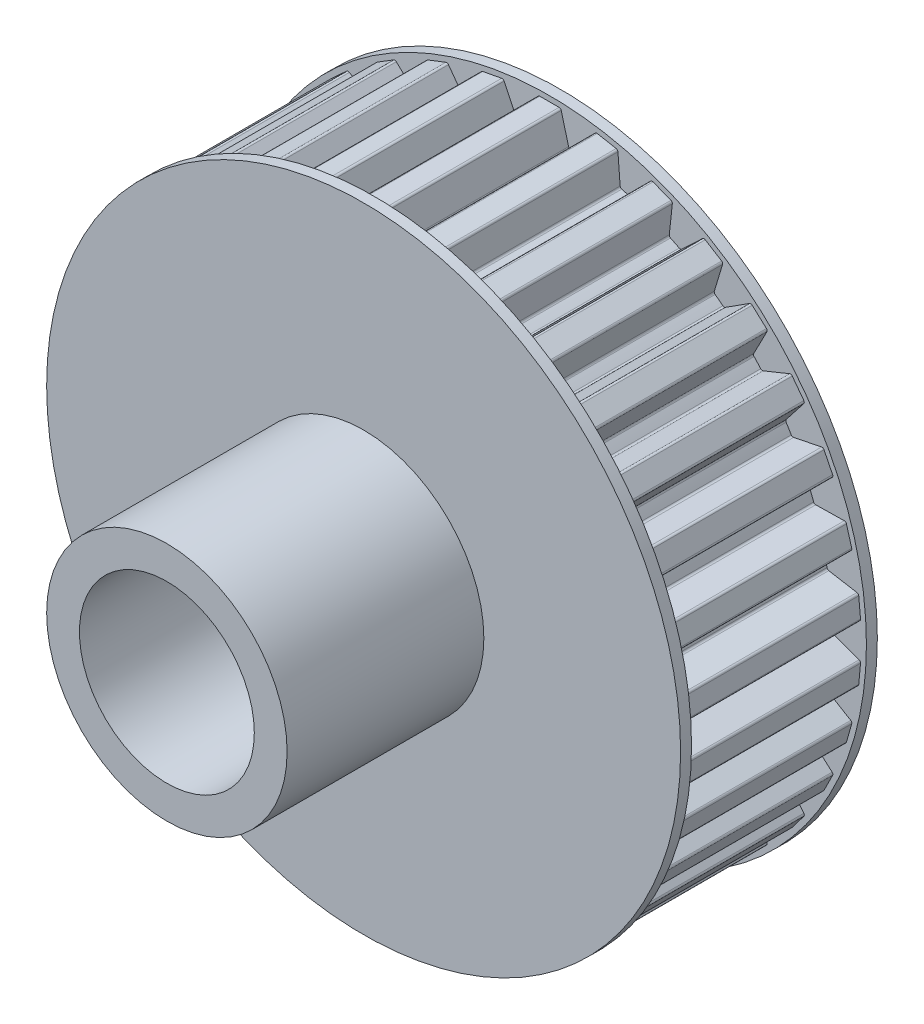
SolidWorks part; units mm, degrees
ref_plane "Plan de face" through (0, 0, 0) normal (0, 0, 1) x (1, 0, 0)
ref_plane "Plan de dessus" through (0, 0, 0) normal (0, 1, 0) x (1, 0, 0)
ref_plane "Plan de droite" through (0, 0, 0) normal (1, 0, 0) x (0, 0, -1)
sketch "Esquisse1" plane through (0, 0, 0) normal (0, 0, 1) x (1, 0, 0)
  line L0 (0, 21.7728) -> (0, 34.0588) construction
  line L1 (-1.0353, 28.5) -> (1.0353, 28.5)
  line L2 (1.0353, 28.5) -> (1.7888, 25.6878)
  line L3 (-25.75, 0) -> (30.4929, 0) construction
  line L4 (0, -28.5) -> (1.0353, -28.5)
  line L5 (0, 28.5) -> (1.7626, 21.9219) construction
  line L6 (-1.0353, 28.5) -> (-1.7888, 25.6878)
  line L7 (4.2192, 28.205) -> (2.9618, 25.5791)
  line L8 (4.2192, 28.205) -> (6.2545, 27.8245)
  line L9 (6.2545, 27.8245) -> (6.4785, 24.9217)
  line L10 (9.33, 26.9494) -> (7.6115, 24.5993)
  line L11 (9.33, 26.9494) -> (11.2608, 26.2015)
  line L12 (11.2608, 26.2015) -> (10.9475, 23.307)
  line L13 (14.1231, 24.7762) -> (12.002, 22.7819)
  line L14 (14.1231, 24.7762) -> (15.8835, 23.6862)
  line L15 (15.8835, 23.6862) -> (15.0438, 20.8985)
  line L16 (18.4352, 21.7592) -> (15.9838, 20.1886)
  line L17 (18.4352, 21.7592) -> (19.9654, 20.3643)
  line L18 (19.9654, 20.3643) -> (18.6277, 17.7784)
  line L19 (22.1196, 18.0013) -> (19.4213, 16.9079)
  line L20 (22.1196, 18.0013) -> (23.3674, 16.3489)
  line L21 (23.3674, 16.3489) -> (21.5773, 14.0529)
  line L22 (25.0507, 13.6303) -> (22.1974, 13.0513)
  line L23 (25.0507, 13.6303) -> (25.9736, 11.7768)
  line L24 (25.9736, 11.7768) -> (23.7921, 9.8488)
  line L25 (27.1287, 8.7952) -> (24.2176, 8.7503)
  line L26 (27.1287, 8.7952) -> (27.6953, 6.8036)
  line L27 (27.6953, 6.8036) -> (25.1967, 5.3093)
  line L28 (28.2829, 3.6605) -> (25.4132, 4.1513)
  line L29 (28.2829, 3.6605) -> (28.4739, 1.5988)
  line L30 (28.4739, 1.5988) -> (25.7433, 0.589)
  line L31 (28.4739, -1.5988) -> (25.7433, -0.589)
  line L32 (28.4739, -1.5988) -> (28.2829, -3.6605)
  line L33 (28.2829, -3.6605) -> (25.4132, -4.1513)
  line L34 (27.6953, -6.8036) -> (25.1967, -5.3093)
  line L35 (27.6953, -6.8036) -> (27.1287, -8.7952)
  line L36 (27.1287, -8.7952) -> (24.2176, -8.7503)
  line L37 (25.9736, -11.7768) -> (23.7921, -9.8488)
  line L38 (25.9736, -11.7768) -> (25.0507, -13.6303)
  line L39 (25.0507, -13.6303) -> (22.1974, -13.0513)
  line L40 (23.3674, -16.3489) -> (21.5773, -14.0529)
  line L41 (23.3674, -16.3489) -> (22.1196, -18.0013)
  line L42 (22.1196, -18.0013) -> (19.4213, -16.9079)
  line L43 (19.9654, -20.3643) -> (18.6277, -17.7784)
  line L44 (19.9654, -20.3643) -> (18.4352, -21.7592)
  line L45 (18.4352, -21.7592) -> (15.9838, -20.1886)
  line L46 (15.8835, -23.6862) -> (15.0438, -20.8985)
  line L47 (15.8835, -23.6862) -> (14.1231, -24.7762)
  line L48 (14.1231, -24.7762) -> (12.002, -22.7819)
  line L49 (11.2608, -26.2015) -> (10.9475, -23.307)
  line L50 (11.2608, -26.2015) -> (9.33, -26.9494)
  line L51 (9.33, -26.9494) -> (7.6115, -24.5993)
  line L52 (6.2545, -27.8245) -> (6.4785, -24.9217)
  line L53 (6.2545, -27.8245) -> (4.2192, -28.205)
  line L54 (4.2192, -28.205) -> (2.9618, -25.5791)
  line L55 (1.0353, -28.5) -> (1.7888, -25.6878)
  line L56 (1.0353, -28.5) -> (-1.0353, -28.5)
  line L57 (-1.0353, -28.5) -> (-1.7888, -25.6878)
  line L58 (-4.2192, -28.205) -> (-2.9618, -25.5791)
  line L59 (-4.2192, -28.205) -> (-6.2545, -27.8245)
  line L60 (-6.2545, -27.8245) -> (-6.4785, -24.9217)
  line L61 (-9.33, -26.9494) -> (-7.6115, -24.5993)
  line L62 (-9.33, -26.9494) -> (-11.2608, -26.2015)
  line L63 (-11.2608, -26.2015) -> (-10.9475, -23.307)
  line L64 (-14.1231, -24.7762) -> (-12.002, -22.7819)
  line L65 (-14.1231, -24.7762) -> (-15.8835, -23.6862)
  line L66 (-15.8835, -23.6862) -> (-15.0438, -20.8985)
  line L67 (-18.4352, -21.7592) -> (-15.9838, -20.1886)
  line L68 (-18.4352, -21.7592) -> (-19.9654, -20.3643)
  line L69 (-19.9654, -20.3643) -> (-18.6277, -17.7784)
  line L70 (-22.1196, -18.0013) -> (-19.4213, -16.9079)
  line L71 (-22.1196, -18.0013) -> (-23.3674, -16.3489)
  line L72 (-23.3674, -16.3489) -> (-21.5773, -14.0529)
  line L73 (-25.0507, -13.6303) -> (-22.1974, -13.0513)
  line L74 (-25.0507, -13.6303) -> (-25.9736, -11.7768)
  line L75 (-25.9736, -11.7768) -> (-23.7921, -9.8488)
  line L76 (-27.1287, -8.7952) -> (-24.2176, -8.7503)
  line L77 (-27.1287, -8.7952) -> (-27.6953, -6.8036)
  line L78 (-27.6953, -6.8036) -> (-25.1967, -5.3093)
  line L79 (-28.2829, -3.6605) -> (-25.4132, -4.1513)
  line L80 (-28.2829, -3.6605) -> (-28.4739, -1.5988)
  line L81 (-28.4739, -1.5988) -> (-25.7433, -0.589)
  line L82 (-28.4739, 1.5988) -> (-25.7433, 0.589)
  line L83 (-28.4739, 1.5988) -> (-28.2829, 3.6605)
  line L84 (-28.2829, 3.6605) -> (-25.4132, 4.1513)
  line L85 (-27.6953, 6.8036) -> (-25.1967, 5.3093)
  line L86 (-27.6953, 6.8036) -> (-27.1287, 8.7952)
  line L87 (-27.1287, 8.7952) -> (-24.2176, 8.7503)
  line L88 (-25.9736, 11.7768) -> (-23.7921, 9.8488)
  line L89 (-25.9736, 11.7768) -> (-25.0507, 13.6303)
  line L90 (-25.0507, 13.6303) -> (-22.1974, 13.0513)
  line L91 (-23.3674, 16.3489) -> (-21.5773, 14.0529)
  line L92 (-23.3674, 16.3489) -> (-22.1196, 18.0013)
  line L93 (-22.1196, 18.0013) -> (-19.4213, 16.9079)
  line L94 (-19.9654, 20.3643) -> (-18.6277, 17.7784)
  line L95 (-19.9654, 20.3643) -> (-18.4352, 21.7592)
  line L96 (-18.4352, 21.7592) -> (-15.9838, 20.1886)
  line L97 (-15.8835, 23.6862) -> (-15.0438, 20.8985)
  line L98 (-15.8835, 23.6862) -> (-14.1231, 24.7762)
  line L99 (-14.1231, 24.7762) -> (-12.002, 22.7819)
  line L100 (-11.2608, 26.2015) -> (-10.9475, 23.307)
  line L101 (-11.2608, 26.2015) -> (-9.33, 26.9494)
  line L102 (-9.33, 26.9494) -> (-7.6115, 24.5993)
  line L103 (-6.2545, 27.8245) -> (-6.4785, 24.9217)
  line L104 (-6.2545, 27.8245) -> (-4.2192, 28.205)
  line L105 (-4.2192, 28.205) -> (-2.9618, 25.5791)
  circle A0 centre (0, 0) radius 6
  arc A1 (-1.7888, 25.6878) -> (-2.9618, 25.5791) centre (0, 0) ccw
  arc A2 (-6.4785, 24.9217) -> (-7.6115, 24.5993) centre (0, 0) ccw
  arc A3 (-10.9475, 23.307) -> (-12.002, 22.7819) centre (0, 0) ccw
  arc A4 (-15.0438, 20.8985) -> (-15.9838, 20.1886) centre (0, 0) ccw
  arc A5 (-18.6277, 17.7784) -> (-19.4213, 16.9079) centre (0, 0) ccw
  arc A6 (-21.5773, 14.0529) -> (-22.1974, 13.0513) centre (0, 0) ccw
  arc A7 (-23.7921, 9.8488) -> (-24.2176, 8.7503) centre (0, 0) ccw
  arc A8 (-25.1967, 5.3093) -> (-25.4132, 4.1513) centre (0, 0) ccw
  arc A9 (-25.7433, 0.589) -> (-25.7433, -0.589) centre (0, 0) ccw
  arc A10 (-25.4132, -4.1513) -> (-25.1967, -5.3093) centre (0, 0) ccw
  arc A11 (-24.2176, -8.7503) -> (-23.7921, -9.8488) centre (0, 0) ccw
  arc A12 (-22.1974, -13.0513) -> (-21.5773, -14.0529) centre (0, 0) ccw
  arc A13 (-19.4213, -16.9079) -> (-18.6277, -17.7784) centre (0, 0) ccw
  arc A14 (-15.9838, -20.1886) -> (-15.0438, -20.8985) centre (0, 0) ccw
  arc A15 (-12.002, -22.7819) -> (-10.9475, -23.307) centre (0, 0) ccw
  arc A16 (-7.6115, -24.5993) -> (-6.4785, -24.9217) centre (0, 0) ccw
  arc A17 (-2.9618, -25.5791) -> (-1.7888, -25.6878) centre (0, 0) ccw
  arc A18 (1.7888, -25.6878) -> (2.9618, -25.5791) centre (0, 0) ccw
  arc A19 (6.4785, -24.9217) -> (7.6115, -24.5993) centre (0, 0) ccw
  arc A20 (10.9475, -23.307) -> (12.002, -22.7819) centre (0, 0) ccw
  arc A21 (15.0438, -20.8985) -> (15.9838, -20.1886) centre (0, 0) ccw
  arc A22 (18.6277, -17.7784) -> (19.4213, -16.9079) centre (0, 0) ccw
  arc A23 (21.5773, -14.0529) -> (22.1974, -13.0513) centre (0, 0) ccw
  arc A24 (23.7921, -9.8488) -> (24.2176, -8.7503) centre (0, 0) ccw
  arc A25 (25.1967, -5.3093) -> (25.4132, -4.1513) centre (0, 0) ccw
  arc A26 (25.7433, -0.589) -> (25.7433, 0.589) centre (0, 0) ccw
  arc A27 (25.4132, 4.1513) -> (25.1967, 5.3093) centre (0, 0) ccw
  arc A28 (24.2176, 8.7503) -> (23.7921, 9.8488) centre (0, 0) ccw
  arc A29 (22.1974, 13.0513) -> (21.5773, 14.0529) centre (0, 0) ccw
  arc A30 (19.4213, 16.9079) -> (18.6277, 17.7784) centre (0, 0) ccw
  arc A31 (15.9838, 20.1886) -> (15.0438, 20.8985) centre (0, 0) ccw
  arc A32 (12.002, 22.7819) -> (10.9475, 23.307) centre (0, 0) ccw
  arc A33 (7.6115, 24.5993) -> (6.4785, 24.9217) centre (0, 0) ccw
  arc A34 (2.9618, 25.5791) -> (1.7888, 25.6878) centre (0, 0) ccw
  point P150 (0, 0)
  dimension "D1" = 12
  dimension "D2" = 51.5
  dimension "D3" = 15
  dimension "D4" = 57
  dimension "D5" = 1
  dimension "D6" = 34
extrude "Boss.-Extru.1" add sketch "Esquisse1" along normal blind 16 contours L6 A1 L2 L1 A0
sketch "Esquisse2" [suppressed] plane through (0, 0, 19) normal (0, 0, 1) x (1, 0, 0)
  circle A0 centre (0, 0) radius 30
  dimension "D1" = 60
extrude "Boss.-Extru.2" [suppressed] add sketch "Esquisse2" along normal blind 2
sketch "Esquisse3" plane through (0, 0, 16) normal (0, 0, 1) x (1, 0, 0)
  circle A0 centre (0, 0) radius 29
  dimension "D1" = 58
extrude "Boss.-Extru.3" add sketch "Esquisse3" along normal blind 1
sketch "Esquisse5" plane through (0, 0, 0) normal (0, 0, -1) x (-1, 0, 0)
  circle A0 centre (0, 0) radius 29
  circle A1 centre (0, 0) radius 6
  dimension "D1" = 12
  dimension "D2" = 58
extrude "Boss.-Extru.4" add sketch "Esquisse5" along normal blind 1
fillet "Congé1" radius 0.2 130 edges at (-2.9618, 25.5791, 8) (-1.7888, 25.6878, 8) (-1.0353, 28.5, 8) (1.0353, 28.5, 8) (-4.2192, 28.205, 8) (-7.6115, 24.5993, 8) (-6.2545, 27.8245, 8) (-6.4785, 24.9217, 8) (-9.33, 26.9494, 8) (-11.2608, 26.2015, 8) (-12.002, 22.7819, 8) (-10.9475, 23.307, 8) (-14.1231, 24.7762, 8) (-15.8835, 23.6862, 8) (-15.9838, 20.1886, 8) (-15.0438, 20.8985, 8) (-18.4352, 21.7592, 8) (-19.9654, 20.3643, 8) (-18.6277, 17.7784, 8) (-19.4213, 16.9079, 8) (-22.1196, 18.0013, 8) (-23.3674, 16.3489, 8) (-21.5773, 14.0529, 8) (-22.1974, 13.0513, 8) (-25.0507, 13.6303, 8) (-24.2176, 8.7503, 8) (-25.9736, 11.7768, 8) (-23.7921, 9.8488, 8) (-27.1287, 8.7952, 8) (-27.6953, 6.8036, 8) (-25.1967, 5.3093, 8) (-25.4132, 4.1513, 8) (-28.2829, 3.6605, 8) (-28.4739, 1.5988, 8) (-25.7433, 0.589, 8) (-25.7433, -0.589, 8) (-28.4739, -1.5988, 8) (-28.2829, -3.6605, 8) (-25.4132, -4.1513, 8) (-25.1967, -5.3093, 8) (-27.6953, -6.8036, 8) (-27.1287, -8.7952, 8) (-24.2176, -8.7503, 8) (-23.7921, -9.8488, 8) (-25.9736, -11.7768, 8) (-25.0507, -13.6303, 8) (-22.1974, -13.0513, 8) (-21.5773, -14.0529, 8) (-23.3674, -16.3489, 8) (-22.1196, -18.0013, 8) (-18.6277, -17.7784, 8) (-19.9654, -20.3643, 8) (-18.4352, -21.7592, 8) (-15.9838, -20.1886, 8) (-15.0438, -20.8985, 8) (-15.8835, -23.6862, 8) (-14.1231, -24.7762, 8) (-12.002, -22.7819, 8) (-10.9475, -23.307, 8) (-11.2608, -26.2015, 8) (-9.33, -26.9494, 8) (-7.6115, -24.5993, 8) (-6.2545, -27.8245, 8) (-4.2192, -28.205, 8) (-1.7888, -25.6878, 8) (-1.0353, -28.5, 8) (2.9618, -25.5791, 8) (1.0353, -28.5, 8) (1.7888, -25.6878, 8) (6.2545, -27.8245, 8) (6.4785, -24.9217, 8) (7.6115, -24.5993, 8) (9.33, -26.9494, 8) (11.2608, -26.2015, 8) (10.9475, -23.307, 8) (12.002, -22.7819, 8) (14.1231, -24.7762, 8) (15.8835, -23.6862, 8) (15.0438, -20.8985, 8) (15.9838, -20.1886, 8) (18.4352, -21.7592, 8) (19.9654, -20.3643, 8) (19.4213, -16.9079, 8) (18.6277, -17.7784, 8) (22.1196, -18.0013, 8) (23.3674, -16.3489, 8) (21.5773, -14.0529, 8) (22.1974, -13.0513, 8) (25.0507, -13.6303, 8) (25.9736, -11.7768, 8) (23.7921, -9.8488, 8) (24.2176, -8.7503, 8) (27.1287, -8.7952, 8) (27.6953, -6.8036, 8) (25.1967, -5.3093, 8) (25.4132, -4.1513, 8) (28.4739, -1.5988, 8) (25.7433, -0.589, 8) (25.7433, 0.589, 8) (28.4739, 1.5988, 8) (28.2829, 3.6605, 8) (25.4132, 4.1513, 8) (25.1967, 5.3093, 8) (27.6953, 6.8036, 8) (27.1287, 8.7952, 8) (24.2176, 8.7503, 8) (23.7921, 9.8488, 8) (25.9736, 11.7768, 8) (25.0507, 13.6303, 8) (22.1974, 13.0513, 8) (21.5773, 14.0529, 8) (23.3674, 16.3489, 8) (22.1196, 18.0013, 8) (19.9654, 20.3643, 8) (19.4213, 16.9079, 8) (18.6277, 17.7784, 8) (15.0438, 20.8985, 8) (15.9838, 20.1886, 8) (10.9475, 23.307, 8) (7.6115, 24.5993, 8) (6.4785, 24.9217, 8) (18.4352, 21.7592, 8) (15.8835, 23.6862, 8) (14.1231, 24.7762, 8) (12.002, 22.7819, 8) (11.2608, 26.2015, 8) (6.2545, 27.8245, 8) (4.2192, 28.205, 8) (2.9618, 25.5791, 8) (1.7888, 25.6878, 8)
sketch "Esquisse6" plane through (0, 0, 17) normal (0, 0, 1) x (1, 0, 0)
  line L1 (-1.5, -1.5) -> (1.5, -1.5)
  line L2 (-1.5, -1.5) -> (-1.5, 1.5)
  line L3 (-1.5, 1.5) -> (1.5, 1.5)
  line L4 (1.5, -1.5) -> (1.5, 1.5)
  line L5 (-1.5, -1.5) -> (1.5, 1.5) construction
  line L6 (-1.5, 1.5) -> (1.5, -1.5) construction
  point P0 (0, 0)
  dimension "D1" = 3
  dimension "D2" = 3
extrude "Enlèv. mat.-Extru.1" cut sketch "Esquisse6" against normal through all
sketch "Esquisse7" plane through (0, 0, 17) normal (0, 0, 1) x (1, 0, 0)
  circle A0 centre (0, 0) radius 11
  circle A1 centre (0, 0) radius 8
  dimension "D1" = 22
  dimension "D2" = 16
extrude "Boss.-Extru.5" add sketch "Esquisse7" along normal blind 18
fillet "Congé2" radius 5 1 edges at (8, 0, 17)
equation "\"D2@Esquisse6\"=\"D1@Esquisse6\""
